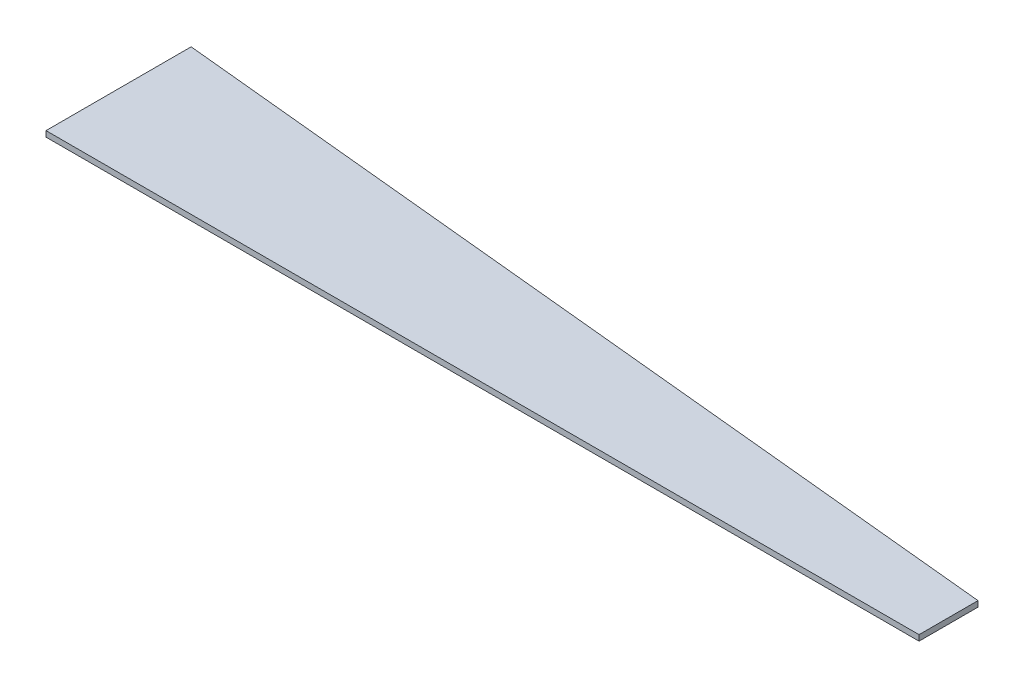
SolidWorks part; units mm, degrees
material "Acrylic (Medium-high impact)"
ref_plane "Front Plane" through (0, 0, 0) normal (0, 0, 1) x (1, 0, 0)
ref_plane "Top Plane" through (0, 0, 0) normal (0, 1, 0) x (1, 0, 0)
ref_plane "Right Plane" through (0, 0, 0) normal (1, 0, 0) x (0, 0, -1)
sketch "Sketch1" plane through (0, 0, 0) normal (0, 1, 0) x (1, 0, 0)
  line L0 (0, 0) -> (488.95, -48.26)
  line L2 (0, 0) -> (0, -81.28)
  line L3 (0, -81.28) -> (488.95, -81.28)
  line L4 (488.95, -48.26) -> (488.95, -81.28)
  dimension "D1" = 33.02
  dimension "D2" = 81.28
extrude "Boss-Extrude1" add sketch "Sketch1" along normal blind 3.175
